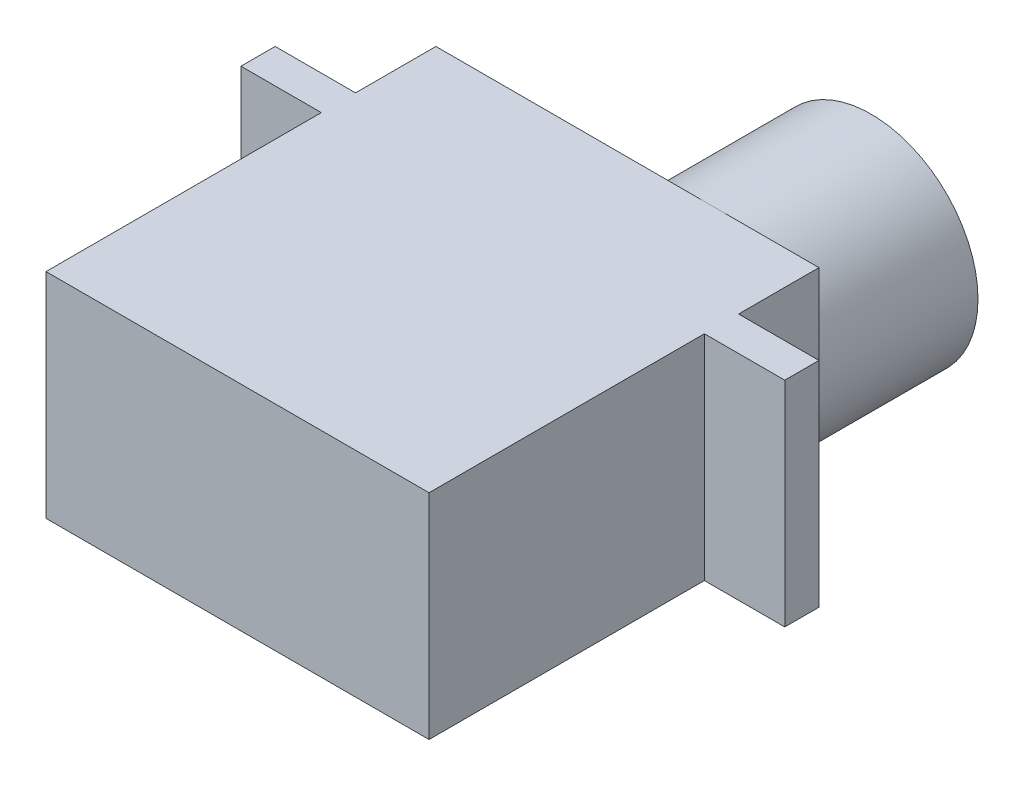
SolidWorks part; units mm, degrees
ref_plane "前视基准面" through (0, 0, 0) normal (0, 0, 1) x (1, 0, 0)
ref_plane "上视基准面" through (0, 0, 0) normal (0, 1, 0) x (1, 0, 0)
ref_plane "右视基准面" through (0, 0, 0) normal (1, 0, 0) x (0, 0, -1)
sketch "草图1" plane through (0, 0, 0) normal (0, 0, 1) x (1, 0, 0)
  line L1 (-11.2, -6.25) -> (11.2, -6.25)
  line L2 (-11.2, -6.25) -> (-11.2, 6.25)
  line L3 (-11.2, 6.25) -> (11.2, 6.25)
  line L4 (11.2, -6.25) -> (11.2, 6.25)
  line L5 (-11.2, -6.25) -> (11.2, 6.25) construction
  line L6 (-11.2, 6.25) -> (11.2, -6.25) construction
  point P0 (0, 0)
  dimension "D1" = 22.4
  dimension "D2" = 12.5
extrude "凸台-拉伸1" add sketch "草图1" along normal blind 16.1 contours L3 L4 L1 L2
sketch "草图2" plane through (0, 0, 0) normal (0, 0, -1) x (-1, 0, 0)
  line L1 (15.9, 6.25) -> (-15.9, 6.25)
  line L2 (15.9, 6.25) -> (15.9, -6.25)
  line L3 (15.9, -6.25) -> (-15.9, -6.25)
  line L4 (-15.9, 6.25) -> (-15.9, -6.25)
  line L5 (15.9, 6.25) -> (-15.9, -6.25) construction
  line L6 (15.9, -6.25) -> (-15.9, 6.25) construction
  point P0 (0, 0)
  dimension "D1" = 12.5
  dimension "D2" = 31.8
extrude "凸台-拉伸2" add sketch "草图2" along normal blind 2
sketch "草图3" plane through (0, 0, -2) normal (0, 0, -1) x (-1, 0, 0)
  line L4 (-15.9, 6.25) -> (-15.9, -6.25)
  line L5 (-15.9, -6.25) -> (15.9, -6.25)
  line L6 (15.9, -6.25) -> (15.9, 6.25)
  line L7 (15.9, 6.25) -> (-15.9, 6.25)
  line L8 (-15.9, 6.25) -> (-15.9, -6.25)
  line L9 (-15.9, -6.25) -> (15.9, -6.25)
  line L10 (15.9, -6.25) -> (15.9, 6.25)
  line L11 (15.9, 6.25) -> (-15.9, 6.25)
  line L12 (11.2, -6.25) -> (11.2, 6.25)
  line L13 (-11.2, -6.25) -> (11.2, -6.25)
  line L14 (-11.2, 6.25) -> (-11.2, -6.25)
  line L15 (11.2, 6.25) -> (-11.2, 6.25)
  line L16 (11.2, -6.25) -> (11.2, 6.25)
  line L17 (-11.2, -6.25) -> (11.2, -6.25)
  line L18 (-11.2, 6.25) -> (-11.2, -6.25)
  line L19 (11.2, 6.25) -> (-11.2, 6.25)
  dimension "D1" = 0
  dimension "D2" = 0
extrude "凸台-拉伸3" add sketch "草图3" along normal blind 4.7 contours L18 L17 L16 L19
sketch "草图4" plane through (0, 0, -6.7) normal (0, 0, -1) x (-1, 0, 0)
  line L0 (11.2, 6.25) -> (-11.2, 6.25) construction
  line L1 (-11.2, 6.25) -> (-11.2, -6.25) construction
  circle A0 centre (-4.95, 0) radius 6.25
  dimension "D3" = 12.5
  dimension "D1" = 6.25
  dimension "D2" = 6.25
extrude "凸台-拉伸4" add sketch "草图4" along normal blind 9.3
